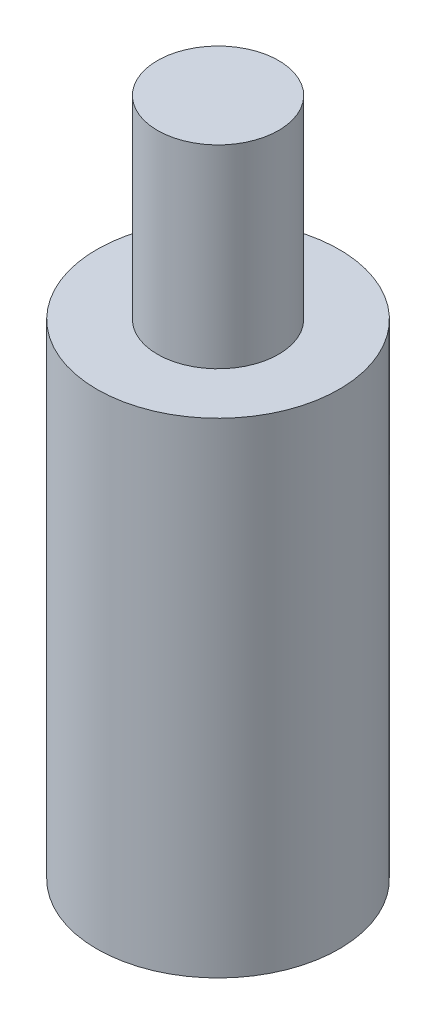
SolidWorks part; units mm, degrees
ref_plane "Front Plane" through (0, 0, 0) normal (0, 0, 1) x (1, 0, 0)
ref_plane "Top Plane" through (0, 0, 0) normal (0, 1, 0) x (1, 0, 0)
ref_plane "Right Plane" through (0, 0, 0) normal (1, 0, 0) x (0, 0, -1)
sketch "Sketch3" plane through (0, 0, 0) normal (0, 1, 0) x (1, 0, 0)
  circle A0 centre (0, 0) radius 3.175
extrude "Boss-Extrude3" add sketch "Sketch3" along normal blind 12.7
sketch "Sketch4" plane through (0, 12.7, 0) normal (0, 1, 0) x (1, 0, 0)
  circle A0 centre (0, 0) radius 1.5875
extrude "Boss-Extrude4" add sketch "Sketch4" along normal blind 5.08
